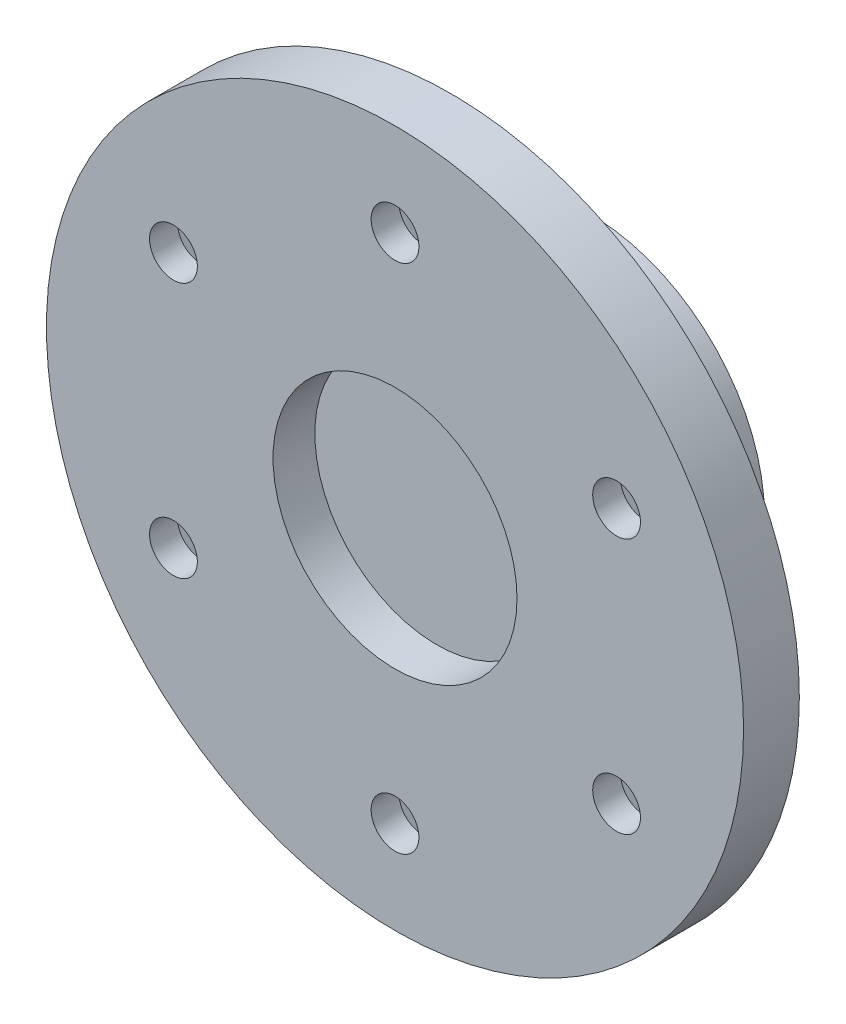
SolidWorks part; units mm, degrees
ref_plane "Front Plane" through (0, 0, 0) normal (0, 0, 1) x (1, 0, 0)
ref_plane "Top Plane" through (0, 0, 0) normal (0, 1, 0) x (1, 0, 0)
ref_plane "Right Plane" through (0, 0, 0) normal (1, 0, 0) x (0, 0, -1)
sketch "Sketch1" plane through (0, 0, 0) normal (0, 0, 1) x (1, 0, 0)
  circle A0 centre (0, 0) radius 25
  dimension "D1" = 50
extrude "Boss-Extrude1" add sketch "Sketch1" along normal blind 4
sketch "Sketch2" plane through (0, 0, 0) normal (0, 0, -1) x (-1, 0, 0)
  line L0 (0, 0) -> (0, 18.35) construction
  circle A0 centre (0, 18.35) radius 1.7136
  circle A1 centre (15.8916, 9.175) radius 1.7136
  circle A2 centre (15.8916, -9.175) radius 1.7136
  circle A3 centre (0, -18.35) radius 1.7136
  circle A4 centre (-15.8916, -9.175) radius 1.7136
  circle A5 centre (-15.8916, 9.175) radius 1.7136
  point P17 (0, 0)
  dimension "D1" = 18.35
  dimension "D2" = 6
extrude "Cut-Extrude1" cut sketch "Sketch2" against normal blind 4
sketch "Sketch3" plane through (0, 0, 0) normal (0, 0, -1) x (-1, 0, 0)
  line L0 (13.8708, 5.675) -> (17.9123, 5.675)
  line L1 (4.0415, 18.35) -> (2.0207, 21.85)
  line L2 (2.0207, 21.85) -> (-2.0207, 21.85)
  line L3 (-2.0207, 21.85) -> (-4.0415, 18.35)
  line L4 (-4.0415, 18.35) -> (-2.0207, 14.85)
  line L5 (-2.0207, 14.85) -> (2.0207, 14.85)
  line L6 (2.0207, 14.85) -> (4.0415, 18.35)
  line L7 (17.9123, 5.675) -> (19.933, 9.175)
  line L8 (19.933, 9.175) -> (17.9123, 12.675)
  line L9 (17.9123, 12.675) -> (13.8708, 12.675)
  line L10 (13.8708, 12.675) -> (11.8501, 9.175)
  line L11 (11.8501, 9.175) -> (13.8708, 5.675)
  line L12 (11.8501, -9.175) -> (13.8708, -12.675)
  line L13 (13.8708, -12.675) -> (17.9123, -12.675)
  line L14 (17.9123, -12.675) -> (19.933, -9.175)
  line L15 (19.933, -9.175) -> (17.9123, -5.675)
  line L16 (17.9123, -5.675) -> (13.8708, -5.675)
  line L17 (13.8708, -5.675) -> (11.8501, -9.175)
  line L18 (-2.0207, -14.85) -> (-4.0415, -18.35)
  line L19 (-4.0415, -18.35) -> (-2.0207, -21.85)
  line L20 (-2.0207, -21.85) -> (2.0207, -21.85)
  line L21 (2.0207, -21.85) -> (4.0415, -18.35)
  line L22 (4.0415, -18.35) -> (2.0207, -14.85)
  line L23 (2.0207, -14.85) -> (-2.0207, -14.85)
  line L24 (-13.8708, -5.675) -> (-17.9123, -5.675)
  line L25 (-17.9123, -5.675) -> (-19.933, -9.175)
  line L26 (-19.933, -9.175) -> (-17.9123, -12.675)
  line L27 (-17.9123, -12.675) -> (-13.8708, -12.675)
  line L28 (-13.8708, -12.675) -> (-11.8501, -9.175)
  line L29 (-11.8501, -9.175) -> (-13.8708, -5.675)
  line L30 (-11.8501, 9.175) -> (-13.8708, 12.675)
  line L31 (-13.8708, 12.675) -> (-17.9123, 12.675)
  line L32 (-17.9123, 12.675) -> (-19.933, 9.175)
  line L33 (-19.933, 9.175) -> (-17.9123, 5.675)
  line L34 (-17.9123, 5.675) -> (-13.8708, 5.675)
  line L35 (-13.8708, 5.675) -> (-11.8501, 9.175)
  circle A0 centre (0, 18.35) radius 3.5 construction
  circle A1 centre (-15.8916, -9.175) radius 1.7136 construction
  circle A2 centre (0, -18.35) radius 1.7136 construction
  circle A3 centre (15.8916, -9.175) radius 1.7136 construction
  circle A4 centre (15.8916, 9.175) radius 1.7136 construction
  point P42 (0, 0)
  dimension "D1" = 7
  dimension "D2" = 6
extrude "Cut-Extrude2" cut sketch "Sketch3" against normal blind 2
sketch "Sketch4" plane through (0, 0, 0) normal (0, 0, -1) x (-1, 0, 0)
  line L0 (0, 0) -> (0, 0.5) construction
  circle A1 centre (0, 0.5) radius 2.5
  circle A2 centre (0, 0) radius 12.5
  dimension "D1" = 5
  dimension "D3" = 25
  dimension "D2" = 0.5
extrude "Boss-Extrude2" add sketch "Sketch4" along normal blind 10
ref_plane "Plane1" through (0, 12.5, 0) normal (0, 1, 0) x (1, 0, 0)
sketch "Sketch5" plane through (0, 12.5, 0) normal (0, 1, 0) x (1, 0, 0)
  circle A0 centre (0, 5) radius 1.6
  dimension "D1" = 3.2
  dimension "D2" = 5
  dimension "D3" = 12.5
extrude "Cut-Extrude3" cut sketch "Sketch5" against normal blind 12.5
sketch "Sketch6" plane through (0, 12.5, 0) normal (0, 1, 0) x (1, 0, 0)
  circle A0 centre (0, 5) radius 3.1
  dimension "D1" = 6.2
extrude "Cut-Extrude4" cut sketch "Sketch6" against normal blind 6
ref_plane "Plane2" through (0, 1.5, 0) normal (0, 1, 0) x (1, 0, 0)
fillet "Fillet1" radius 1.5 1 edges at (12.5, 0, 0)
sketch "Sketch9" plane through (0, 0, 4) normal (0, 0, 1) x (1, 0, 0)
  circle A0 centre (0, 0) radius 8.75
  dimension "D1" = 17.5
extrude "Cut-Extrude6" cut sketch "Sketch9" against normal blind 3
sketch "Sketch12" plane through (0, 0, -10) normal (0, 0, -1) x (-1, 0, 0)
  line L2 (1.2231, -3.8816) -> (3.9731, 0.8816)
  line L3 (3.9731, 0.8816) -> (6.1381, -0.3684)
  line L4 (6.1381, -0.3684) -> (3.3881, -5.1316)
  line L5 (3.3881, -5.1316) -> (1.2231, -3.8816)
  line L6 (-2.75, 4.5) -> (2.75, 4.5)
  line L7 (-2.75, 4.5) -> (-2.75, 2)
  line L8 (-2.75, 2) -> (2.75, 2)
  line L9 (2.75, 4.5) -> (2.75, 2)
  line L10 (0, 0.5) -> (0, -6.5) construction
  line L11 (-3.3881, -5.1316) -> (-1.2231, -3.8816)
  line L12 (-6.1381, -0.3684) -> (-3.3881, -5.1316)
  line L13 (-3.9731, 0.8816) -> (-6.1381, -0.3684)
  line L14 (-1.2231, -3.8816) -> (-3.9731, 0.8816)
  circle A0 centre (0, 0) radius 12.5 construction
  point P1 (0, 2)
  point P2 (2.5981, -1.5)
  point P22 (2.8441, -1.2383)
  dimension "D1" = 5.5
  dimension "D2" = 2
  dimension "D3" = 3
  dimension "D4" = 2.5
  dimension "D5" = 5.5
  dimension "D6" = 2.5
  dimension "D7" = 2.75
extrude "Cut-Extrude7" cut sketch "Sketch12" against normal blind 10
ref_plane "Plane3" through (-6.1381, -0.3684, -10) normal (-0.5, 0.866, 0) x (0.866, 0.5, 0)
sketch "Sketch16" plane through (0, 0, -10) normal (0, 0, -1) x (-1, 0, 0)
  line L0 (-2.5981, -1.5) -> (-10.8253, -6.25)
  line L1 (-1.2231, -3.8816) -> (-3.9731, 0.8816) construction
  line L2 (-2.5981, -1.5) -> (-1.9158, -1.1061)
  circle A0 centre (0, 0) radius 12.5 construction
  arc A1 (-2, 2) -> (2, 2) centre (0, 0.5) ccw construction
sketch "Sketch17" plane through (2.5981, -1.5, 0) normal (0.866, -0.5, 0) x (0, 0, -1)
  line L0 (10, 0) -> (5, 0)
  line L1 (10, -2.75) -> (10, 2.75) construction
  circle A0 centre (5, 0) radius 1.6
  dimension "D3" = 3.2
  dimension "D1" = 5
  dimension "D2" = 0
  dimension "D4" = 0
extrude "Cut-Extrude8" cut sketch "Sketch17" along normal blind 10 and the other way blind 2
sketch "Sketch18" plane through (-2.5981, -1.5, 0) normal (-0.866, -0.5, 0) x (0, 0, 1)
  line L0 (-10, 0) -> (-5, 0)
  line L1 (-10, 2.75) -> (-10, -2.75) construction
  circle A0 centre (-5, 0) radius 1.6
  dimension "D3" = 3.2
  dimension "D1" = 5
  dimension "D2" = 0
extrude "Cut-Extrude9" cut sketch "Sketch18" against normal blind 2 and the other way blind 30
sketch "Sketch20" plane through (-4.7631, -2.75, 0) normal (0.866, 0.5, 0) x (0, 0, -1)
  circle A0 centre (5, 0) radius 3.1
  dimension "D1" = 6.2
extrude "Cut-Extrude10" cut sketch "Sketch20" against normal blind 4 from offset 3 offset against normal yes
sketch "Sketch21" plane through (4.7631, -2.75, 0) normal (-0.866, 0.5, 0) x (0, 0, 1)
  circle A0 centre (-5, 0) radius 3.1
  dimension "D1" = 6.2
extrude "Cut-Extrude11" cut sketch "Sketch21" against normal blind 4 from offset 3
equation "\"mm\"=1.5"
